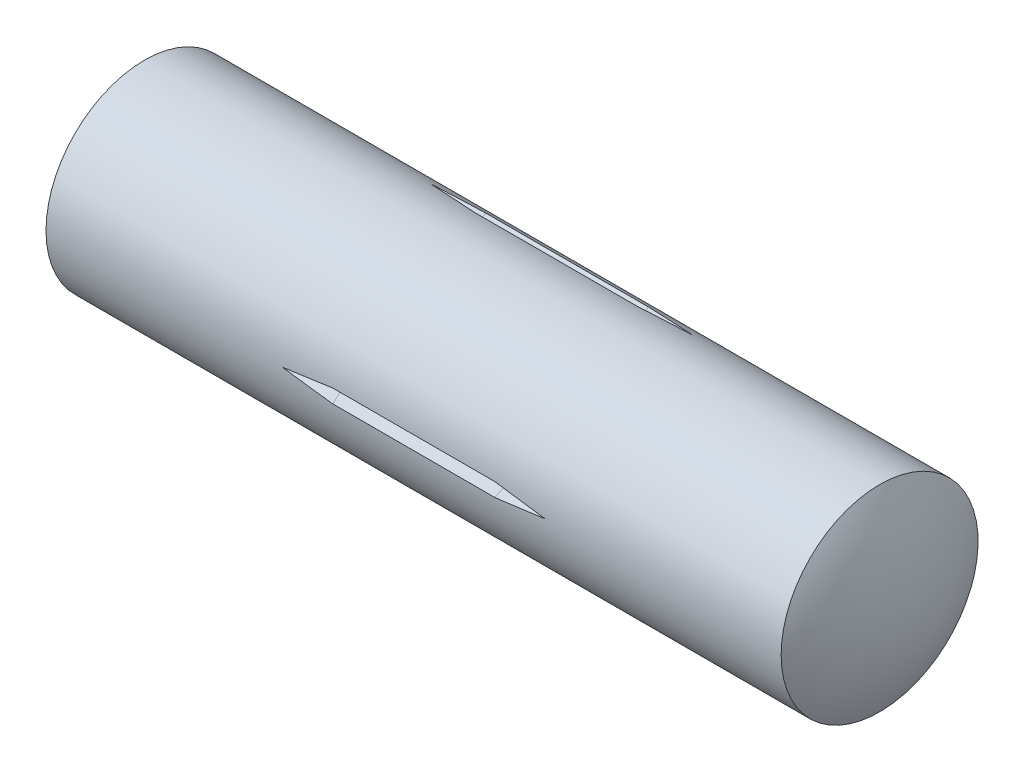
SolidWorks part; units mm, degrees
ref_plane "Plane1" through (0, 0, 0) normal (0, 0, 1) x (1, 0, 0)
ref_plane "Plane2" through (0, 0, 0) normal (0, 1, 0) x (1, 0, 0)
ref_plane "Plane3" through (0, 0, 0) normal (1, 0, 0) x (0, 0, -1)
sketch "Sketch1" plane through (0, 0, 0) normal (0, 0, 1) x (1, 0, 0)
  line L0 (-57, 0) -> (60, 0) construction
  line L1 (-50, 0) -> (-50, 1.25)
  line L2 (-46.6819, 12.5) -> (46.6506, 12.5)
  line L3 (-50, 0) -> (50, 0)
  arc A0 (-46.6819, 12.5) -> (-50, 1.25) centre (-25.0313, 0) ccw
  arc A1 (50, 0) -> (46.6506, 12.5) centre (25, 0) ccw
  dimension "D1" = 25
  dimension "D2" = 25
  dimension "Diameter" = 25
  dimension "Length" = 100
  dimension "D3" = 2.5
revolve "Base-Revolve" add sketch "Sketch1" angle 360 about L0
sketch "Sketch3" plane through (0, 0, 0) normal (0, 1, 0) x (1, 0, 0)
  line L0 (0, 0) -> (60, 0) construction
  line L1 (-57, 0) -> (60, 0) construction
  line L2 (-16.6667, -12.5) -> (-10.4167, -11.25)
  line L3 (-10.4167, -11.25) -> (10.4167, -11.25)
  line L4 (10.4167, -11.25) -> (16.6667, -12.5)
  dimension "D1" = 25
  dimension "D2" = 33.3333
  dimension "D3" = 16.6667
  dimension "D4" = 22.5
  dimension "D5" = 6.25
  dimension "D6" = 6.25
ref_plane "Plane4" through (-16.6667, 0, 0) normal (1, 0, 0) x (0, 0, -1)
sketch "Sketch4" plane through (-16.6667, 0, 0) normal (1, 0, 0) x (0, 0, -1)
  line L0 (0, 0) -> (-14, 0) construction
  line L1 (-12.5, 0) -> (-14.3784, 1.3152)
  line L2 (-12.5, 0) -> (-14.3784, -1.3152)
  line L3 (-14.3784, -1.3152) -> (-14.3784, 1.3152)
  circle A0 centre (0, 0) radius 12.5 construction
  dimension "D1" = 25
  dimension "D2" = 70
  dimension "D3" = 35
  dimension "D4" = 1.8784
sweep "Cut-Sweep3" cut profiles "Sketch4" path "Sketch3"
pattern_circular "CirPattern2" count 3 over 360 about axis through (0, 0, 0) along (1, 0, 0) of "Cut-Sweep3"
equation "\"D1@Sketch1\" = \"Diameter@Sketch1\""
equation "\"D2@Sketch1\" = \"Diameter@Sketch1\""
equation "\"D3@Sketch1\" = \"Diameter@Sketch1\" * .1"
equation "\"D1@Sketch3\" = \"Diameter@Sketch1\""
equation "\"D2@Sketch3\" = \"Length@Sketch1\" / 3"
equation "\"D3@Sketch3\" = \"D2@Sketch3\" / 2"
equation "\"D4@Sketch3\" = \"Diameter@Sketch1\" * .9"
equation "\"D5@Sketch3\" = \"D1@Sketch1\" / 4"
equation "\"D6@Sketch3\" = \"D5@Sketch3\""
equation "\"D1@Plane4\" = \"D3@Sketch3\""
equation "\"D1@Sketch4\" = \"Diameter@Sketch1\""
equation "\"D3@Sketch4\" = \"D2@Sketch4\" / 2"
